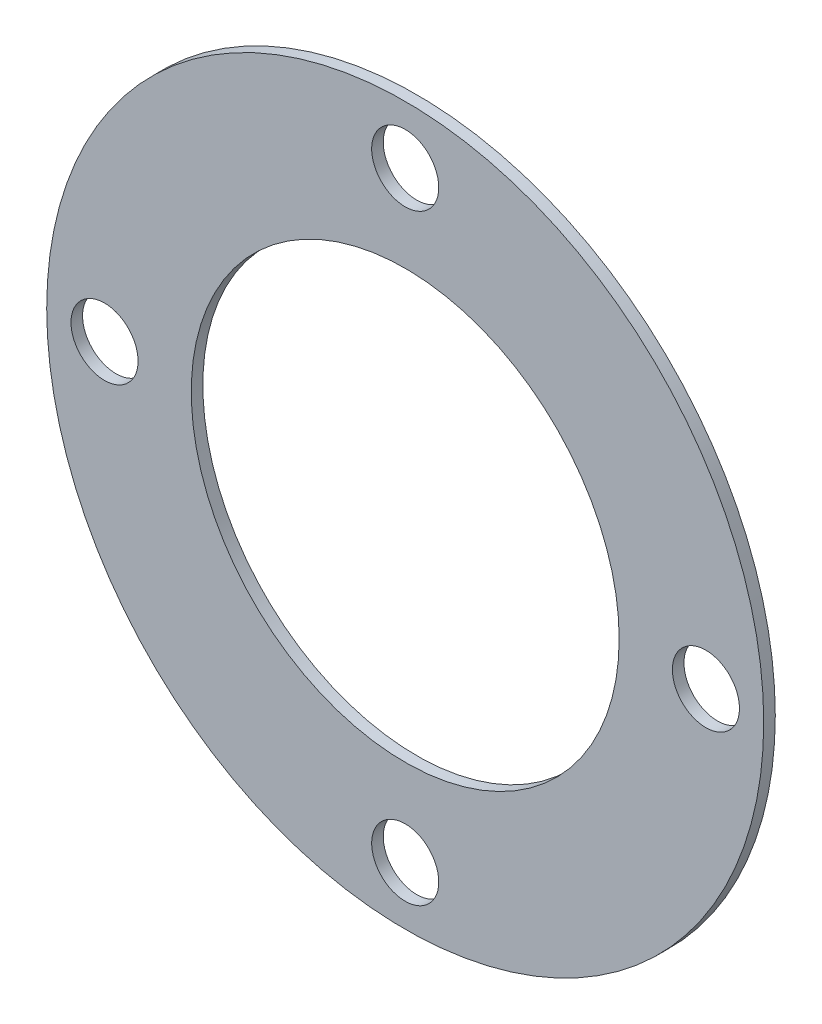
SolidWorks part; units mm, degrees
ref_plane "Front Plane" through (0, 0, 0) normal (0, 0, 1) x (1, 0, 0)
ref_plane "Top Plane" through (0, 0, 0) normal (0, 1, 0) x (1, 0, 0)
ref_plane "Right Plane" through (0, 0, 0) normal (1, 0, 0) x (0, 0, -1)
sketch "Sketch1" plane through (0, 0, 0) normal (0, 0, 1) x (1, 0, 0)
  circle A0 centre (0, 0) radius 31
  circle A1 centre (0, 0) radius 18.5
  dimension "D1" = 62
  dimension "D2" = 37
extrude "Boss-Extrude1" add sketch "Sketch1" along normal blind 1
hole_wizard "M5 Clearance Hole1" positions "Sketch2" profile "Sketch3" hole size "M5" standard "ISO" end condition through all
sketch "Sketch2" plane through (0, 0, 1) normal (0, 0, 1) x (1, 0, 0)
  point P0 (26, 0)
  point P3 (0, 26)
  point P6 (-26, 0)
  point P9 (0, -26)
sketch "Sketch3" plane through (26, 0, 1) normal (1, 0, 0) x (0, -1, 0)
  line L0 (0, 0) -> (0, 1)
  line L1 (0, 1) -> (2.9, 1)
  line L2 (2.9, 1) -> (2.9, 0)
  line L5 (2.9, 0) -> (0, 0)
  line L11 (0, -6.35) -> (0, 107.95) construction
  dimension "Thru Hole Dia." = 5.8
  dimension "Thru Hole Depth" = 1
